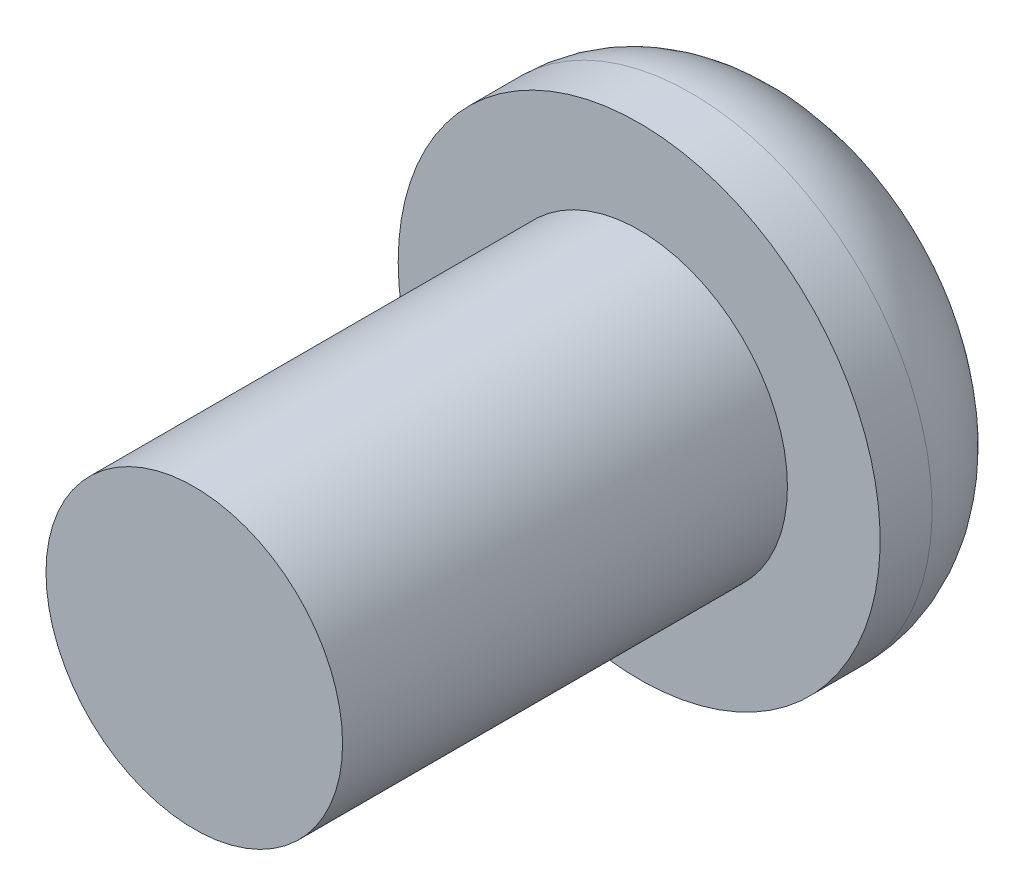
SolidWorks part; units mm, degrees
ref_plane "前视基准面" through (0, 0, 0) normal (0, 0, 1) x (1, 0, 0)
ref_plane "上视基准面" through (0, 0, 0) normal (0, 1, 0) x (1, 0, 0)
ref_plane "右视基准面" through (0, 0, 0) normal (1, 0, 0) x (0, 0, -1)
sketch "草图1" plane through (0, 0, 0) normal (0, 0, 1) x (1, 0, 0)
  circle A0 centre (0, 0) radius 2
extrude "凸台-拉伸1" add sketch "草图1" along normal blind 6
sketch "草图2" plane through (0, 0, 0) normal (0, 0, -1) x (-1, 0, 0)
  circle A0 centre (0, 0) radius 3.25
extrude "凸台-拉伸2" add sketch "草图2" along normal blind 2.2
fillet "圆角1" radius 1.5 1 edges at (-3.25, 0, -2.2)
